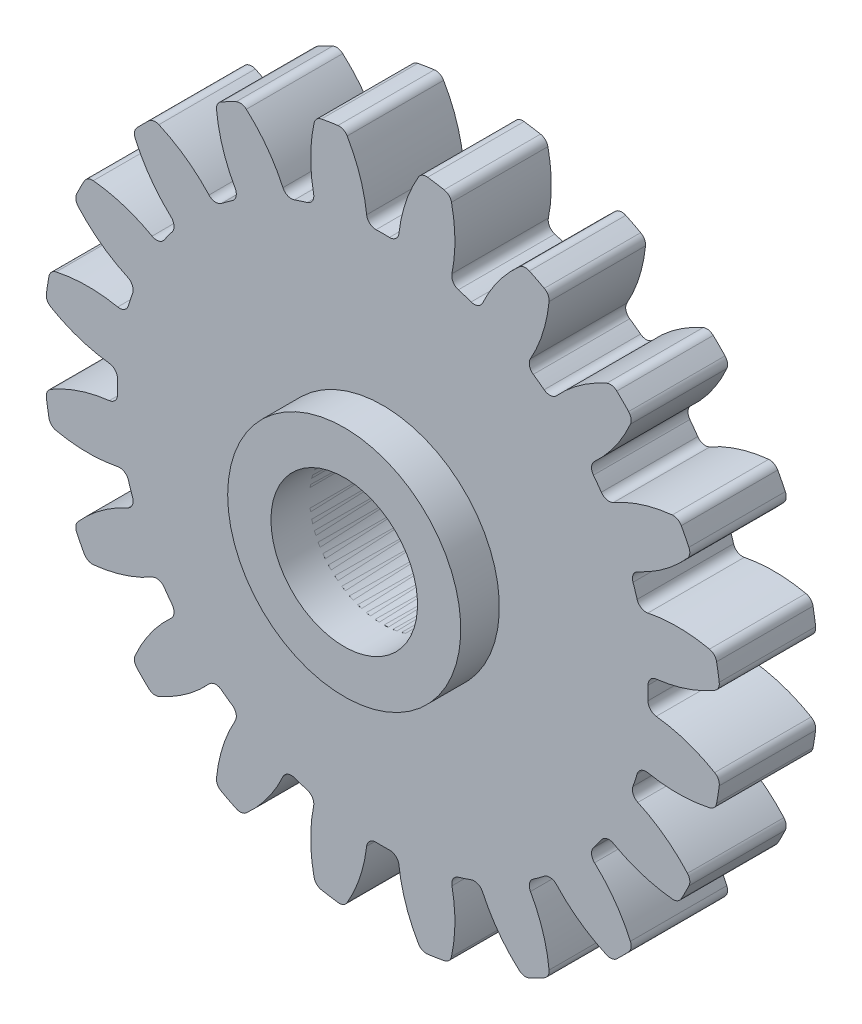
SolidWorks part; units mm, degrees
other "Markup1"
sketch "Sketch17" plane through (-10.9062, 10.9062, 11.3) normal (-0.0184, 0.3965, 0.9179) x (0.5503, 0.7705, -0.3218)
ref_plane "Front Plane" through (0, 0, 0) normal (0, 0, 1) x (1, 0, 0)
ref_plane "Top Plane" through (0, 0, 0) normal (0, 1, 0) x (1, 0, 0)
ref_plane "Right Plane" through (0, 0, 0) normal (1, 0, 0) x (0, 0, -1)
sketch "Sketch1" plane through (0, 0, 0) normal (0, 0, 1) x (1, 0, 0)
  circle A2 centre (0, 0) radius 16
  circle A3 centre (0, 0) radius 17.6
  circle A4 centre (0, 0) radius 13.76
  dimension "D1" = 32
  dimension "D2" = 35.2
  dimension "D3" = 3.84
extrude "Boss-Extrude1" add sketch "Sketch1" along normal mid plane 5 contours A3
sketch "Sketch3" plane through (0, 0, 2.5) normal (0, 0, 1) x (1, 0, 0)
  line L0 (0, 0) -> (0, 17.6) construction
  line L1 (-1.2553, 15.9507) -> (1.2553, 15.9507) construction
  line L2 (0, 0) -> (-0.7984, 13.7368) construction
  line L3 (0, 12.5016) -> (-2.1733, 18.4726) construction
  line L4 (0, 0) -> (2.7532, 17.3833) construction
  line L5 (1.2553, 15.9507) -> (3.7351, 15.5579) construction
  circle A0 centre (0, 0) radius 17.6 construction
  arc A1 (-2.701, 18.4028) -> (-0.7984, 13.7368) centre (-8.5805, 13.2845) cw
  arc A2 (2.701, 18.4028) -> (0.7984, 13.7368) centre (8.5805, 13.2845) ccw
  circle A3 centre (0, 0) radius 13.76 construction
  arc A4 (0.7984, 13.7368) -> (-0.7984, 13.7368) centre (0, 0) ccw
  circle A5 centre (0, 0) radius 16 construction
  circle A6 centre (0, 0) radius 17.6 construction
  circle A7 centre (0, 0) radius 18.6
  arc A8 (2.701, 18.4028) -> (-2.701, 18.4028) centre (0, 0) ccw
  dimension "D2" = 20
  dimension "D3" = 9
extrude "Cut-Extrude1" cut sketch "Sketch3" against normal through all both and the other way through all
fillet "Fillet1" radius 0.48 4 edges at (0.7984, 13.7368, 0) (-0.7984, 13.7368, 0) (2.0134, 17.4845, 0) (-2.0134, 17.4845, 0)
pattern_circular "CirPattern1" count 20 over 360 about axis through (0, 0, 0) along (0, 0, 1) of "Cut-Extrude1", "Fillet1"
sketch "Sketch23" plane through (0, 0, -2.5) normal (0, 0, -1) x (-1, 0, 0)
  circle A0 centre (0, 0) radius 3.25
extrude "Cut-Extrude9" cut sketch "Sketch23" against normal blind 0.7
sketch "Sketch24" plane through (0, 0, 2.5) normal (0, 0, 1) x (1, 0, 0)
  circle A0 centre (0, 0) radius 4
  dimension "D1" = 8
extrude "Cut-Extrude10" cut sketch "Sketch24" against normal blind 10
sketch "Sketch25" plane through (0, 0, 2.5) normal (0, 0, 1) x (1, 0, 0)
  circle A0 centre (0, 0) radius 4.6038
extrude "Boss-Extrude2" add sketch "Sketch25" against normal through all
sketch "Sketch26" plane through (0, 0, -2.5) normal (0, 0, -1) x (-1, 0, 0)
  circle A0 centre (0, 0) radius 3.8
  dimension "D1" = 7.6
extrude "Cut-Extrude11" cut sketch "Sketch26" against normal blind 10
sketch "Sketch27" plane through (0, 0, -2.5) normal (0, 0, -1) x (-1, 0, 0)
  circle A0 centre (0, 0) radius 6.0443
  circle A1 centre (0, 0) radius 3.8
extrude "Boss-Extrude3" add sketch "Sketch27" along normal blind 2 and the other way blind 7 separate body
equation "\"Module\"= 1.6mm"
equation "\"Number of Teeth\"= 20"
equation "\"D1@Sketch1\"=\"Module\" * \"Number of Teeth\""
equation "\"D2@Sketch1\"=(\"Number of Teeth\" + 2) * \"Module\""
equation "\"D3@Sketch1\"=\"Module\" * if( \"Module\"=>1.25,2.25,2.4)"
equation "\"D3@Sketch3\"=180 / \"Number of Teeth\""
equation "\"D1@Fillet1\"=0.3 * \"Module\""
equation "\"D1@CirPattern1\"=\"Number of Teeth\""
